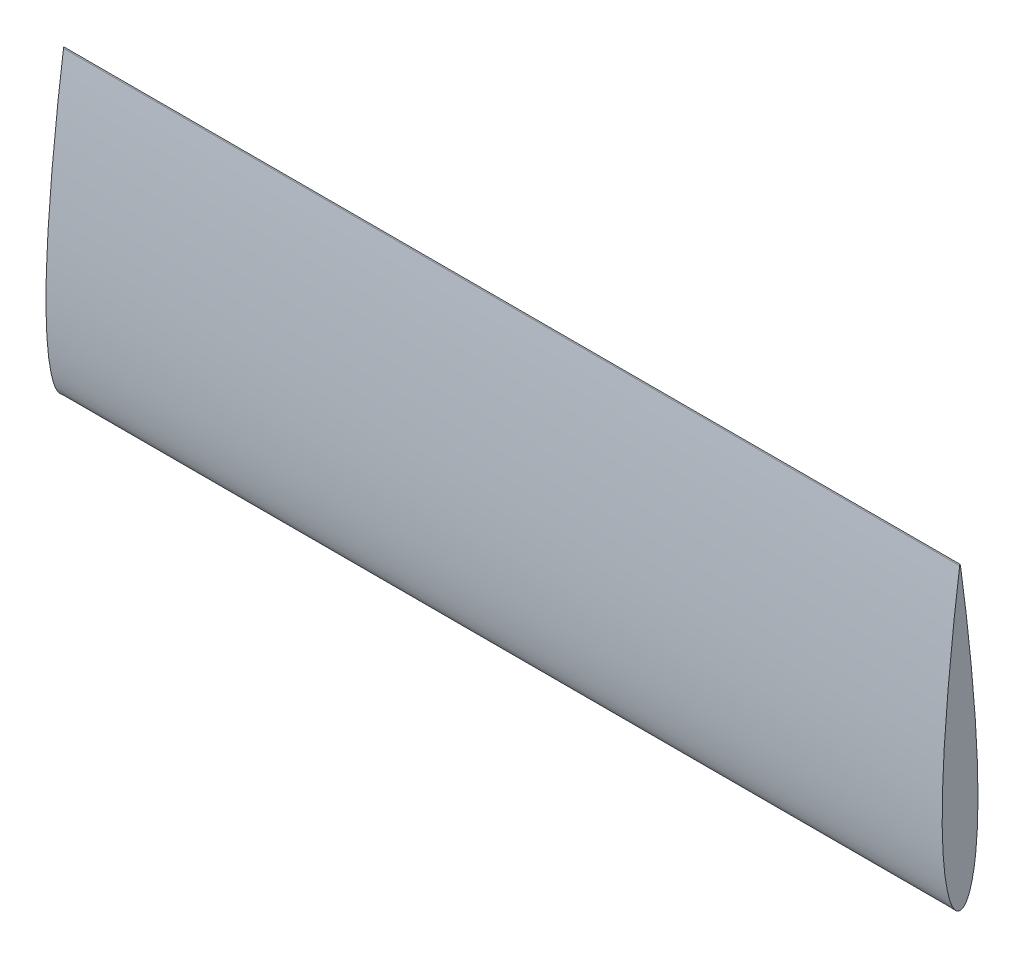
SolidWorks part; units mm, degrees
ref_plane "Front Plane" through (0, 0, 0) normal (0, 0, 1) x (1, 0, 0)
ref_plane "Top Plane" through (0, 0, 0) normal (0, 1, 0) x (1, 0, 0)
ref_plane "Right Plane" through (0, 0, 0) normal (1, 0, 0) x (0, 0, -1)
curve "Curve1"
  spline degree 3 poles (0, 200, 0.252) (0, 199.9611, 0.2575) (0, 199.8055, 0.2793) (0, 199.4557, 0.3283) (0, 198.8736, 0.4096) (0, 198.0607, 0.5226) (0, 197.0187, 0.6667) (0, 195.7501, 0.8408) (0, 194.2579, 1.044) (0, 192.5455, 1.2748) (0, 190.617, 1.532) (0, 188.4769, 1.814) (0, 186.1302, 2.1191) (0, 183.5822, 2.4456) (0, 180.8391, 2.7917) (0, 177.9071, 3.1555) (0, 174.7932, 3.5353) (0, 171.5046, 3.9289) (0, 168.0491, 4.3345) (0, 164.4345, 4.75) (0, 160.6695, 5.1736) (0, 156.7628, 5.603) (0, 152.7235, 6.0365) (0, 148.5611, 6.4717) (0, 144.2853, 6.9067) (0, 139.906, 7.3392) (0, 135.4336, 7.7672) (0, 130.8784, 8.1882) (0, 126.251, 8.6001) (0, 121.5624, 9.0004) (0, 116.8234, 9.3867) (0, 112.0451, 9.7565) (0, 107.2386, 10.1074) (0, 102.4153, 10.4366) (0, 97.5863, 10.7416) (0, 92.7629, 11.0198) (0, 87.9565, 11.2686) (0, 83.1781, 11.4855) (0, 78.439, 11.6681) (0, 73.7502, 11.814) (0, 69.1227, 11.9211) (0, 64.5673, 11.9873) (0, 60.0946, 12.0108) (0, 55.7151, 11.9901) (0, 51.439, 11.924) (0, 47.2762, 11.8115) (0, 43.2365, 11.6519) (0, 39.3293, 11.4449) (0, 35.5638, 11.1905) (0, 31.9486, 10.8891) (0, 28.4923, 10.5414) (0, 25.2029, 10.1484) (0, 22.088, 9.7115) (0, 19.1549, 9.2321) (0, 16.4104, 8.7122) (0, 13.8607, 8.1538) (0, 11.5118, 7.5591) (0, 9.3688, 6.9302) (0, 7.4367, 6.2696) (0, 5.7193, 5.5794) (0, 4.2203, 4.8617) (0, 2.9422, 4.1182) (0, 1.8869, 3.3496) (0, 1.0559, 2.5553) (0, 0.452, 1.7324) (0, 0.0824, 0.8774) (0, -0.0402, 0) (0, 0.0824, -0.8774) (0, 0.452, -1.7324) (0, 1.0559, -2.5553) (0, 1.8869, -3.3496) (0, 2.9422, -4.1182) (0, 4.2203, -4.8617) (0, 5.7193, -5.5794) (0, 7.4367, -6.2696) (0, 9.3688, -6.9302) (0, 11.5118, -7.5591) (0, 13.8607, -8.1538) (0, 16.4104, -8.7122) (0, 19.1549, -9.2321) (0, 22.088, -9.7115) (0, 25.2029, -10.1484) (0, 28.4923, -10.5414) (0, 31.9486, -10.8891) (0, 35.5638, -11.1905) (0, 39.3293, -11.4449) (0, 43.2365, -11.6519) (0, 47.2762, -11.8115) (0, 51.439, -11.924) (0, 55.7151, -11.9901) (0, 60.0946, -12.0108) (0, 64.5673, -11.9873) (0, 69.1227, -11.9211) (0, 73.7502, -11.814) (0, 78.439, -11.6681) (0, 83.1781, -11.4855) (0, 87.9565, -11.2686) (0, 92.7629, -11.0198) (0, 97.5863, -10.7416) (0, 102.4153, -10.4366) (0, 107.2386, -10.1074) (0, 112.0451, -9.7565) (0, 116.8234, -9.3867) (0, 121.5624, -9.0004) (0, 126.251, -8.6001) (0, 130.8784, -8.1882) (0, 135.4336, -7.7672) (0, 139.906, -7.3392) (0, 144.2853, -6.9067) (0, 148.5611, -6.4717) (0, 152.7235, -6.0365) (0, 156.7628, -5.603) (0, 160.6695, -5.1736) (0, 164.4345, -4.75) (0, 168.0491, -4.3345) (0, 171.5046, -3.9289) (0, 174.7932, -3.5353) (0, 177.9071, -3.1555) (0, 180.8391, -2.7917) (0, 183.5822, -2.4456) (0, 186.1302, -2.1191) (0, 188.4769, -1.814) (0, 190.617, -1.532) (0, 192.5455, -1.2748) (0, 194.2579, -1.044) (0, 195.7501, -0.8408) (0, 197.0187, -0.6667) (0, 198.0607, -0.5226) (0, 198.8736, -0.4096) (0, 199.4557, -0.3283) (0, 199.8055, -0.2793) (0, 199.9611, -0.2575) (0, 200, -0.252) knots 0 0 0 0 0.000289 0.001156 0.002598 0.004612 0.007194 0.010336 0.014031 0.018271 0.023046 0.028343 0.03415 0.040454 0.047239 0.054489 0.062186 0.070314 0.078852 0.08778 0.097077 0.106722 0.116691 0.126961 0.137507 0.148306 0.159331 0.170557 0.181957 0.193504 0.205172 0.216932 0.228758 0.240621 0.252495 0.26435 0.276161 0.287898 0.299536 0.311047 0.322405 0.333584 0.344559 0.355306 0.3658 0.376018 0.385938 0.395538 0.404798 0.413699 0.422222 0.430349 0.438066 0.445357 0.452209 0.458611 0.464554 0.47003 0.475035 0.479569 0.483637 0.48725 0.490431 0.493219 0.495674 0.497891 0.5 0.502109 0.504326 0.506781 0.509569 0.51275 0.516363 0.520431 0.524965 0.52997 0.535446 0.541389 0.547791 0.554643 0.561934 0.569651 0.577778 0.586301 0.595202 0.604462 0.614062 0.623982 0.6342 0.644694 0.655441 0.666416 0.677595 0.688953 0.700464 0.712102 0.723839 0.73565 0.747505 0.759379 0.771242 0.783068 0.794828 0.806496 0.818043 0.829443 0.840669 0.851694 0.862493 0.873039 0.883309 0.893278 0.902923 0.91222 0.921148 0.929686 0.937814 0.945511 0.952761 0.959546 0.96585 0.971657 0.976954 0.981729 0.985969 0.989664 0.992806 0.995388 0.997402 0.998844 0.999711 1 1 1 1
sketch "Sketch1" plane through (0, 0, 0) normal (1, 0, 0) x (0, 0, -1)
  spline S0 degree 3 poles (-2950.4525, 735.5122) (13.8221, 279.2587) (5.3001, 239.659) (-0.3283, 199.4557) (-0.4096, 198.8736) (-0.5226, 198.0607) (-0.6667, 197.0187) (-0.8408, 195.7501) (-1.044, 194.2579) (-1.2748, 192.5455) (-1.532, 190.617) (-1.814, 188.4769) (-2.1191, 186.1302) (-2.4456, 183.5822) (-2.7917, 180.8391) (-3.1555, 177.9071) (-3.5353, 174.7932) (-3.9289, 171.5046) (-4.3345, 168.0491) (-4.75, 164.4345) (-5.1736, 160.6695) (-5.603, 156.7628) (-6.1894, 151.298) (-6.7695, 145.6747) (-7.3392, 139.906) (-7.7672, 135.4336) (-8.1882, 130.8784) (-8.6001, 126.251) (-9.0004, 121.5624) (-9.3867, 116.8234) (-9.7565, 112.0451) (-10.1074, 107.2386) (-10.4366, 102.4153) (-10.7416, 97.5863) (-11.0198, 92.7629) (-11.2686, 87.9565) (-11.4855, 83.1781) (-11.6681, 78.439) (-11.814, 73.7502) (-11.9211, 69.1227) (-11.9873, 64.5673) (-12.0108, 60.0946) (-11.9901, 55.7151) (-11.924, 51.439) (-11.8115, 47.2762) (-11.6519, 43.2365) (-11.4449, 39.3293) (-11.1905, 35.5638) (-10.8891, 31.9486) (-10.5414, 28.4923) (-10.1484, 25.2029) (-9.7115, 22.088) (-9.2321, 19.1549) (-8.7122, 16.4104) (-8.1538, 13.8607) (-7.5591, 11.5118) (-6.9302, 9.3688) (-6.2696, 7.4367) (-5.5794, 5.7193) (-4.8617, 4.2203) (-4.1182, 2.9422) (-3.3496, 1.8869) (-2.5553, 1.0559) (-1.7324, 0.452) (-0.8774, 0.0824) (0, -0.0402) (0.8774, 0.0824) (1.7324, 0.452) (2.5553, 1.0559) (3.3496, 1.8869) (4.1182, 2.9422) (4.8617, 4.2203) (5.5794, 5.7193) (6.2696, 7.4367) (6.9302, 9.3688) (7.5591, 11.5118) (8.1538, 13.8607) (8.7122, 16.4104) (9.2321, 19.1549) (9.7115, 22.088) (10.1484, 25.2029) (10.5414, 28.4923) (10.8891, 31.9486) (11.1905, 35.5638) (11.4449, 39.3293) (11.6519, 43.2365) (11.8115, 47.2762) (11.924, 51.439) (11.9901, 55.7151) (12.0108, 60.0946) (11.9873, 64.5673) (11.9211, 69.1227) (11.814, 73.7502) (11.6681, 78.439) (11.4855, 83.1781) (11.2686, 87.9565) (11.0198, 92.7629) (10.7416, 97.5863) (10.4366, 102.4153) (10.1074, 107.2386) (9.7565, 112.0451) (9.3867, 116.8234) (9.0004, 121.5624) (8.6001, 126.251) (8.1882, 130.8784) (7.632, 136.8953) (6.9232, 144.1838) (6.1894, 151.298) (5.603, 156.7628) (5.1736, 160.6695) (4.75, 164.4345) (4.3345, 168.0491) (3.9289, 171.5046) (3.5353, 174.7932) (3.1555, 177.9071) (2.7917, 180.8391) (2.4456, 183.5822) (2.1191, 186.1302) (1.814, 188.4769) (1.532, 190.617) (1.2748, 192.5455) (1.044, 194.2579) (0.8408, 195.7501) (0.6667, 197.0187) (0.5226, 198.0607) (0.4096, 198.8736) (0.3283, 199.4557) (-5.2999, 239.6576) (-13.8215, 279.2559) (2950.14, 735.4642) knots -0.29602 -0.29602 -0.29602 -0.29602 0.000289 0.001156 0.002598 0.004612 0.007194 0.010336 0.014031 0.018271 0.023046 0.028343 0.03415 0.040454 0.047239 0.054489 0.062186 0.070314 0.078852 0.08778 0.097077 0.106722 0.116691 0.137507 0.148306 0.159331 0.170557 0.181957 0.193504 0.205172 0.216932 0.228758 0.240621 0.252495 0.26435 0.276161 0.287898 0.299536 0.311047 0.322405 0.333584 0.344559 0.355306 0.3658 0.376018 0.385938 0.395538 0.404798 0.413699 0.422222 0.430349 0.438066 0.445357 0.452209 0.458611 0.464554 0.47003 0.475035 0.479569 0.483637 0.48725 0.490431 0.493219 0.495674 0.497891 0.5 0.502109 0.504326 0.506781 0.509569 0.51275 0.516363 0.520431 0.524965 0.52997 0.535446 0.541389 0.547791 0.554643 0.561934 0.569651 0.577778 0.586301 0.595202 0.604462 0.614062 0.623982 0.6342 0.644694 0.655441 0.666416 0.677595 0.688953 0.700464 0.712102 0.723839 0.73565 0.747505 0.759379 0.771242 0.783068 0.794828 0.806496 0.818043 0.829443 0.840669 0.862493 0.883309 0.893278 0.902923 0.91222 0.921148 0.929686 0.937814 0.945511 0.952761 0.959546 0.96585 0.971657 0.976954 0.981729 0.985969 0.989664 0.992806 0.995388 0.997402 0.998844 0.999711 1.29601 1.29601 1.29601 1.29601 only from (-0.252, 200) to (0.252, 200) construction
  spline S1 degree 3 poles (-0.252, 200) (-0.2575, 199.9611) (-0.2793, 199.8055) (-0.3283, 199.4557) (-0.4096, 198.8736) (-0.5226, 198.0607) (-0.6667, 197.0187) (-0.8408, 195.7501) (-1.044, 194.2579) (-1.2748, 192.5455) (-1.532, 190.617) (-1.814, 188.4769) (-2.1191, 186.1302) (-2.4456, 183.5822) (-2.7917, 180.8391) (-3.1555, 177.9071) (-3.5353, 174.7932) (-3.9289, 171.5046) (-4.3345, 168.0491) (-4.75, 164.4345) (-5.1736, 160.6695) (-5.603, 156.7628) (-6.1894, 151.298) (-6.7695, 145.6747) (-7.3392, 139.906) (-7.7672, 135.4336) (-8.1882, 130.8784) (-8.6001, 126.251) (-9.0004, 121.5624) (-9.3867, 116.8234) (-9.7565, 112.0451) (-10.1074, 107.2386) (-10.4366, 102.4153) (-10.7416, 97.5863) (-11.0198, 92.7629) (-11.2686, 87.9565) (-11.4855, 83.1781) (-11.6681, 78.439) (-11.814, 73.7502) (-11.9211, 69.1227) (-11.9873, 64.5673) (-12.0108, 60.0946) (-11.9901, 55.7151) (-11.924, 51.439) (-11.8115, 47.2762) (-11.6519, 43.2365) (-11.4449, 39.3293) (-11.1905, 35.5638) (-10.8891, 31.9486) (-10.5414, 28.4923) (-10.1484, 25.2029) (-9.7115, 22.088) (-9.2321, 19.1549) (-8.7122, 16.4104) (-8.1538, 13.8607) (-7.5591, 11.5118) (-6.9302, 9.3688) (-6.2696, 7.4367) (-5.5794, 5.7193) (-4.8617, 4.2203) (-4.1182, 2.9422) (-3.3496, 1.8869) (-2.5553, 1.0559) (-1.7324, 0.452) (-0.8774, 0.0824) (0, -0.0402) (0.8774, 0.0824) (1.7324, 0.452) (2.5553, 1.0559) (3.3496, 1.8869) (4.1182, 2.9422) (4.8617, 4.2203) (5.5794, 5.7193) (6.2696, 7.4367) (6.9302, 9.3688) (7.5591, 11.5118) (8.1538, 13.8607) (8.7122, 16.4104) (9.2321, 19.1549) (9.7115, 22.088) (10.1484, 25.2029) (10.5414, 28.4923) (10.8891, 31.9486) (11.1905, 35.5638) (11.4449, 39.3293) (11.6519, 43.2365) (11.8115, 47.2762) (11.924, 51.439) (11.9901, 55.7151) (12.0108, 60.0946) (11.9873, 64.5673) (11.9211, 69.1227) (11.814, 73.7502) (11.6681, 78.439) (11.4855, 83.1781) (11.2686, 87.9565) (11.0198, 92.7629) (10.7416, 97.5863) (10.4366, 102.4153) (10.1074, 107.2386) (9.7565, 112.0451) (9.3867, 116.8234) (9.0004, 121.5624) (8.6001, 126.251) (8.1882, 130.8784) (7.632, 136.8953) (6.9232, 144.1838) (6.1894, 151.298) (5.603, 156.7628) (5.1736, 160.6695) (4.75, 164.4345) (4.3345, 168.0491) (3.9289, 171.5046) (3.5353, 174.7932) (3.1555, 177.9071) (2.7917, 180.8391) (2.4456, 183.5822) (2.1191, 186.1302) (1.814, 188.4769) (1.532, 190.617) (1.2748, 192.5455) (1.044, 194.2579) (0.8408, 195.7501) (0.6667, 197.0187) (0.5226, 198.0607) (0.4096, 198.8736) (0.3283, 199.4557) (0.2808, 199.7948) (0.2605, 199.9397) (0.2565, 199.9679) knots 0 0 0 0 0.000289 0.001156 0.002598 0.004612 0.007194 0.010336 0.014031 0.018271 0.023046 0.028343 0.03415 0.040454 0.047239 0.054489 0.062186 0.070314 0.078852 0.08778 0.097077 0.106722 0.116691 0.137507 0.148306 0.159331 0.170557 0.181957 0.193504 0.205172 0.216932 0.228758 0.240621 0.252495 0.26435 0.276161 0.287898 0.299536 0.311047 0.322405 0.333584 0.344559 0.355306 0.3658 0.376018 0.385938 0.395538 0.404798 0.413699 0.422222 0.430349 0.438066 0.445357 0.452209 0.458611 0.464554 0.47003 0.475035 0.479569 0.483637 0.48725 0.490431 0.493219 0.495674 0.497891 0.5 0.502109 0.504326 0.506781 0.509569 0.51275 0.516363 0.520431 0.524965 0.52997 0.535446 0.541389 0.547791 0.554643 0.561934 0.569651 0.577778 0.586301 0.595202 0.604462 0.614062 0.623982 0.6342 0.644694 0.655441 0.666416 0.677595 0.688953 0.700464 0.712102 0.723839 0.73565 0.747505 0.759379 0.771242 0.783068 0.794828 0.806496 0.818043 0.829443 0.840669 0.862493 0.883309 0.893278 0.902923 0.91222 0.921148 0.929686 0.937814 0.945511 0.952761 0.959546 0.96585 0.971657 0.976954 0.981729 0.985969 0.989664 0.992806 0.995388 0.997402 0.998844 0.999711 0.99992 0.99992 0.99992 0.99992
  spline S2 degree 2 poles (-0.252, 200) (-0.2253, 201.7743) (0.2565, 199.9679) knots 0 0 0 1 1 1
extrude "Boss-Extrude1" add sketch "Sketch1" along normal mid plane 600
